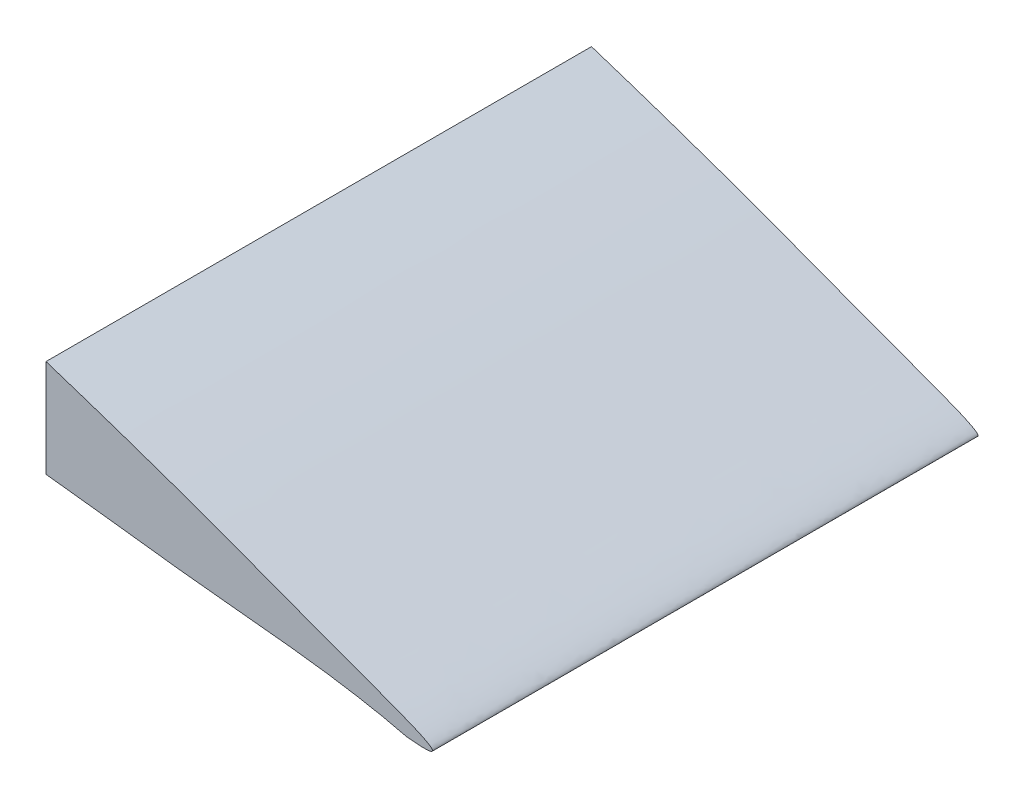
SolidWorks part; units mm, degrees
ref_plane "Front Plane" through (0, 0, 0) normal (0, 0, 1) x (1, 0, 0)
ref_plane "Top Plane" through (0, 0, 0) normal (0, 1, 0) x (1, 0, 0)
ref_plane "Right Plane" through (0, 0, 0) normal (1, 0, 0) x (0, 0, -1)
sketch "Sketch1" plane through (0, 0, 0) normal (0, 0, 1) x (1, 0, 0)
  spline S0 degree 3 poles (0.0006, 0.0001) (0.8106, 7.3592) (8.6491, 17.8566) (26.2867, 29.9752) (52.1111, 42.0692) (89.5976, 49.2908) (131.4008, 47.8848) (173.2567, 40.0411) (217.9611, 29.613) (256.9521, 19.5289) (290.3598, 8.711) (301.2732, 4.3828) (314.8169, -0.5162) (309.8463, 0.0001) knots 0 0 0 0 0.060864 0.113688 0.188609 0.312909 0.448482 0.557612 0.691544 0.852438 0.929756 0.976058 1 1 1 1
  spline S1 degree 3 poles (309.8463, 0.0001) (303.9568, 1.471) (293.9895, 2.094) (276.264, 4.5144) (260.8463, 5.4274) (235.8588, 7.8703) (205.1014, 8.8381) (157.7186, 9.0307) (110.4973, 6.1815) (66.5062, -0.5867) (36.4547, -6.0985) (15.3166, -6.1891) (1.2307, -6.9241) (0.0006, 0.0001) knots 0 0 0 0 0.057787 0.095275 0.171021 0.205339 0.335319 0.464904 0.658702 0.785512 0.893517 0.943092 1 1 1 1
extrude "Boss-Extrude1" add sketch "Sketch1" along normal blind 46.0375
sketch "Sketch2" plane through (0, 0, 46.0375) normal (0, 0, 1) x (1, 0, 0)
  circle A0 centre (20.32, 10.16) radius 6.35
  circle A1 centre (227.2963, 19.0501) radius 3.175
  dimension "D2" = 12.7
  dimension "D3" = 6.35
  dimension "D6" = 20.32
  dimension "D1" = 82.55
  dimension "D4" = 19.05
  dimension "D5" = 10.16
extrude "Cut-Extrude1" cut sketch "Sketch2" against normal through all
sketch "Sketch4" plane through (0, 0, 46.0375) normal (0, 0, 1) x (1, 0, 0)
  line L1 (279.4006, -24.2166) -> (-9.5632, -24.2166)
  line L2 (279.4006, -24.2166) -> (279.4006, 93.2727)
  line L3 (279.4006, 93.2727) -> (-9.5632, 93.2727)
  line L4 (-9.5632, -24.2166) -> (-9.5632, 93.2727)
  dimension "D1" = 279.4
extrude "Cut-Extrude3" cut sketch "Sketch4" against normal through all
